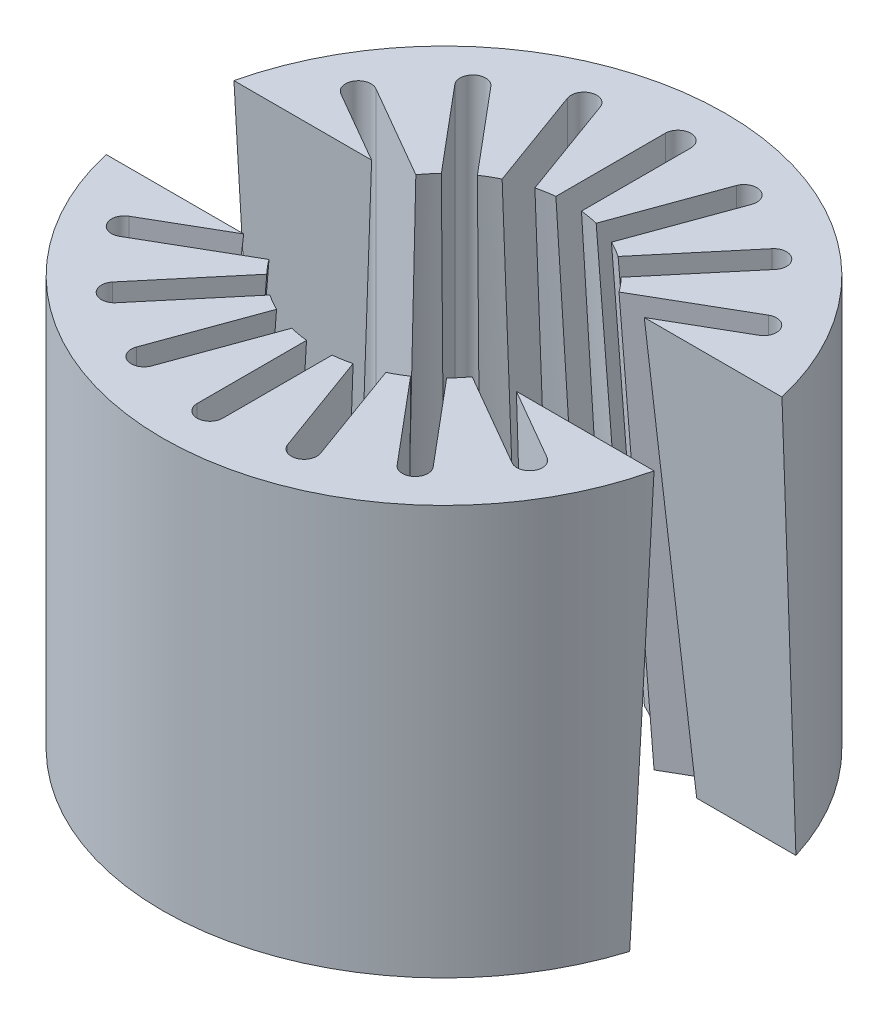
SolidWorks part; units mm, degrees
ref_plane "Front Plane" through (0, 0, 0) normal (0, 0, 1) x (1, 0, 0)
ref_plane "Top Plane" through (0, 0, 0) normal (0, 1, 0) x (1, 0, 0)
ref_plane "Right Plane" through (0, 0, 0) normal (1, 0, 0) x (0, 0, -1)
sketch "Sketch1" plane through (0, 0, 0) normal (0, 1, 0) x (1, 0, 0)
  line L1 (11, -7.5) -> (-11, -7.5) construction
  line L2 (11, -7.5) -> (11, 7.5) construction
  line L3 (11, 7.5) -> (-11, 7.5) construction
  line L4 (-11, -7.5) -> (-11, 7.5) construction
  line L5 (11, -7.5) -> (-11, 7.5) construction
  line L6 (11, 7.5) -> (-11, -7.5) construction
  circle A0 centre (0, 0) radius 5 construction
  circle A1 centre (0, 0) radius 11
  point P0 (0, 0)
  dimension "D1" = 10
  dimension "D2" = 22
  dimension "D3" = 15
extrude "Boss-Extrude1" add sketch "Sketch1" along normal blind 16
sketch "Sketch2" plane through (0, 0, 0) normal (1, 0, 0) x (0, 0, -1)
  line L0 (0, 0) -> (0, 16)
  line L2 (0, 16) -> (4.9, 16)
  line L3 (4.9, 16) -> (5.9, 0)
  line L5 (5.9, 0) -> (0, 0)
  line L6 (11, 16) -> (-11, 16) construction
  line L7 (-11, 0) -> (11, 0) construction
  point P3 (0, 0)
  point P5 (0, 0)
  point P12 (0, 0)
  point P13 (0, 0)
  dimension "D1" = 4.9
  dimension "5.9" = 5.9
revolve "Cut-Revolve1" cut sketch "Sketch2" angle 360 about L0
sketch "Sketch3" plane through (0, 16, 0) normal (0, 1, 0) x (1, 0, 0)
  line L0 (0, 4.8) -> (0, 0) construction
  line L1 (-0.5, 4.8) -> (0.5, 4.8)
  line L2 (-0.5, 4.8) -> (-0.5, 9.15)
  line L4 (0.5, 4.8) -> (0.5, 9.15)
  line L5 (1.1719, 4.6815) -> (2.1115, 4.3395)
  line L6 (1.1719, 4.6815) -> (2.6596, 8.7692)
  line L7 (2.1115, 4.3395) -> (3.5993, 8.4272)
  line L8 (2.7024, 3.9984) -> (3.4684, 3.3556)
  line L9 (2.7024, 3.9984) -> (5.4985, 7.3307)
  line L10 (3.4684, 3.3556) -> (6.2645, 6.6879)
  line L11 (3.9069, 2.833) -> (4.4069, 1.967)
  line L12 (3.9069, 2.833) -> (7.6741, 5.008)
  line L13 (4.4069, 1.967) -> (8.1741, 4.142)
  line L14 (4.6403, 1.3259) -> (4.8139, 0.3411)
  line L15 (4.6403, 1.3259) -> (8.9242, 2.0813)
  line L16 (4.8139, 0.3411) -> (9.0978, 1.0965)
  line L17 (4.8139, -0.3411) -> (4.6403, -1.3259)
  line L18 (4.8139, -0.3411) -> (9.0978, -1.0965)
  line L19 (4.6403, -1.3259) -> (8.9242, -2.0813)
  line L20 (4.4069, -1.967) -> (3.9069, -2.833)
  line L21 (4.4069, -1.967) -> (8.1741, -4.142)
  line L22 (3.9069, -2.833) -> (7.6741, -5.008)
  line L23 (3.4684, -3.3556) -> (2.7024, -3.9984)
  line L24 (3.4684, -3.3556) -> (6.2645, -6.6879)
  line L25 (2.7024, -3.9984) -> (5.4985, -7.3307)
  line L26 (2.1115, -4.3395) -> (1.1719, -4.6815)
  line L27 (2.1115, -4.3395) -> (3.5993, -8.4272)
  line L28 (1.1719, -4.6815) -> (2.6596, -8.7692)
  line L29 (0.5, -4.8) -> (-0.5, -4.8)
  line L30 (0.5, -4.8) -> (0.5, -9.15)
  line L31 (-0.5, -4.8) -> (-0.5, -9.15)
  line L32 (-1.1719, -4.6815) -> (-2.1115, -4.3395)
  line L33 (-1.1719, -4.6815) -> (-2.6596, -8.7692)
  line L34 (-2.1115, -4.3395) -> (-3.5993, -8.4272)
  line L35 (-2.7024, -3.9984) -> (-3.4684, -3.3556)
  line L36 (-2.7024, -3.9984) -> (-5.4985, -7.3307)
  line L37 (-3.4684, -3.3556) -> (-6.2645, -6.6879)
  line L38 (-3.9069, -2.833) -> (-4.4069, -1.967)
  line L39 (-3.9069, -2.833) -> (-7.6741, -5.008)
  line L40 (-4.4069, -1.967) -> (-8.1741, -4.142)
  line L41 (-4.6403, -1.3259) -> (-4.8139, -0.3411)
  line L42 (-4.6403, -1.3259) -> (-8.9242, -2.0813)
  line L43 (-4.8139, -0.3411) -> (-9.0978, -1.0965)
  line L44 (-4.8139, 0.3411) -> (-4.6403, 1.3259)
  line L45 (-4.8139, 0.3411) -> (-9.0978, 1.0965)
  line L46 (-4.6403, 1.3259) -> (-8.9242, 2.0813)
  line L47 (-4.4069, 1.967) -> (-3.9069, 2.833)
  line L48 (-4.4069, 1.967) -> (-8.1741, 4.142)
  line L49 (-3.9069, 2.833) -> (-7.6741, 5.008)
  line L50 (-3.4684, 3.3556) -> (-2.7024, 3.9984)
  line L51 (-3.4684, 3.3556) -> (-6.2645, 6.6879)
  line L52 (-2.7024, 3.9984) -> (-5.4985, 7.3307)
  line L53 (-2.1115, 4.3395) -> (-1.1719, 4.6815)
  line L54 (-2.1115, 4.3395) -> (-3.5993, 8.4272)
  line L55 (-1.1719, 4.6815) -> (-2.6596, 8.7692)
  arc A0 (0, 9.65) -> (0.5, 9.15) centre (0, 9.15) cw
  arc A1 (-0.5, 9.15) -> (0, 9.65) centre (0, 9.15) cw
  arc A2 (3.3005, 9.068) -> (3.5993, 8.4272) centre (3.1295, 8.5982) cw
  arc A3 (2.6596, 8.7692) -> (3.3005, 9.068) centre (3.1295, 8.5982) cw
  arc A4 (6.2029, 7.3923) -> (6.2645, 6.6879) centre (5.8815, 7.0093) cw
  arc A5 (5.4985, 7.3307) -> (6.2029, 7.3923) centre (5.8815, 7.0093) cw
  arc A6 (8.3571, 4.825) -> (8.1741, 4.142) centre (7.9241, 4.575) cw
  arc A7 (7.6741, 5.008) -> (8.3571, 4.825) centre (7.9241, 4.575) cw
  arc A8 (9.5034, 1.6757) -> (9.0978, 1.0965) centre (9.011, 1.5889) cw
  arc A9 (8.9242, 2.0813) -> (9.5034, 1.6757) centre (9.011, 1.5889) cw
  arc A10 (9.5034, -1.6757) -> (8.9242, -2.0813) centre (9.011, -1.5889) cw
  arc A11 (9.0978, -1.0965) -> (9.5034, -1.6757) centre (9.011, -1.5889) cw
  arc A12 (8.3571, -4.825) -> (7.6741, -5.008) centre (7.9241, -4.575) cw
  arc A13 (8.1741, -4.142) -> (8.3571, -4.825) centre (7.9241, -4.575) cw
  arc A14 (6.2029, -7.3923) -> (5.4985, -7.3307) centre (5.8815, -7.0093) cw
  arc A15 (6.2645, -6.6879) -> (6.2029, -7.3923) centre (5.8815, -7.0093) cw
  arc A16 (3.3005, -9.068) -> (2.6596, -8.7692) centre (3.1295, -8.5982) cw
  arc A17 (3.5993, -8.4272) -> (3.3005, -9.068) centre (3.1295, -8.5982) cw
  arc A18 (0, -9.65) -> (-0.5, -9.15) centre (0, -9.15) cw
  arc A19 (0.5, -9.15) -> (0, -9.65) centre (0, -9.15) cw
  arc A20 (-3.3005, -9.068) -> (-3.5993, -8.4272) centre (-3.1295, -8.5982) cw
  arc A21 (-2.6596, -8.7692) -> (-3.3005, -9.068) centre (-3.1295, -8.5982) cw
  arc A22 (-6.2029, -7.3923) -> (-6.2645, -6.6879) centre (-5.8815, -7.0093) cw
  arc A23 (-5.4985, -7.3307) -> (-6.2029, -7.3923) centre (-5.8815, -7.0093) cw
  arc A24 (-8.3571, -4.825) -> (-8.1741, -4.142) centre (-7.9241, -4.575) cw
  arc A25 (-7.6741, -5.008) -> (-8.3571, -4.825) centre (-7.9241, -4.575) cw
  arc A26 (-9.5034, -1.6757) -> (-9.0978, -1.0965) centre (-9.011, -1.5889) cw
  arc A27 (-8.9242, -2.0813) -> (-9.5034, -1.6757) centre (-9.011, -1.5889) cw
  arc A28 (-9.5034, 1.6757) -> (-8.9242, 2.0813) centre (-9.011, 1.5889) cw
  arc A29 (-9.0978, 1.0965) -> (-9.5034, 1.6757) centre (-9.011, 1.5889) cw
  arc A30 (-8.3571, 4.825) -> (-7.6741, 5.008) centre (-7.9241, 4.575) cw
  arc A31 (-8.1741, 4.142) -> (-8.3571, 4.825) centre (-7.9241, 4.575) cw
  arc A32 (-6.2029, 7.3923) -> (-5.4985, 7.3307) centre (-5.8815, 7.0093) cw
  arc A33 (-6.2645, 6.6879) -> (-6.2029, 7.3923) centre (-5.8815, 7.0093) cw
  arc A34 (-3.3005, 9.068) -> (-2.6596, 8.7692) centre (-3.1295, 8.5982) cw
  arc A35 (-3.5993, 8.4272) -> (-3.3005, 9.068) centre (-3.1295, 8.5982) cw
  point P131 (0, 0)
  dimension "D1" = 0.5
  dimension "D2" = 4.35
  dimension "D3" = 4.8
  dimension "D4" = 1
  dimension "D5" = 18
extrude "Cut-Extrude1" cut sketch "Sketch3" against normal through all
sketch "Sketch4" plane through (0, 0, 0) normal (1, 0, 0) x (0, 0, -1)
  line L0 (0, 16) -> (0, 0) construction
  line L1 (11, 16) -> (-11, 16) construction
  line L2 (0, 16) -> (2.5, 16)
  line L3 (2.5, 16) -> (3.25, 0)
  line L4 (-11, 0) -> (11, 0) construction
  line L5 (3.25, 0) -> (-3.25, 0)
  line L6 (-3.25, 0) -> (-2.5, 16)
  line L7 (-2.5, 16) -> (0, 16)
  dimension "D1" = 5
  dimension "D2" = 6.5
extrude "Cut-Extrude2" cut sketch "Sketch4" against normal mid plane 30
